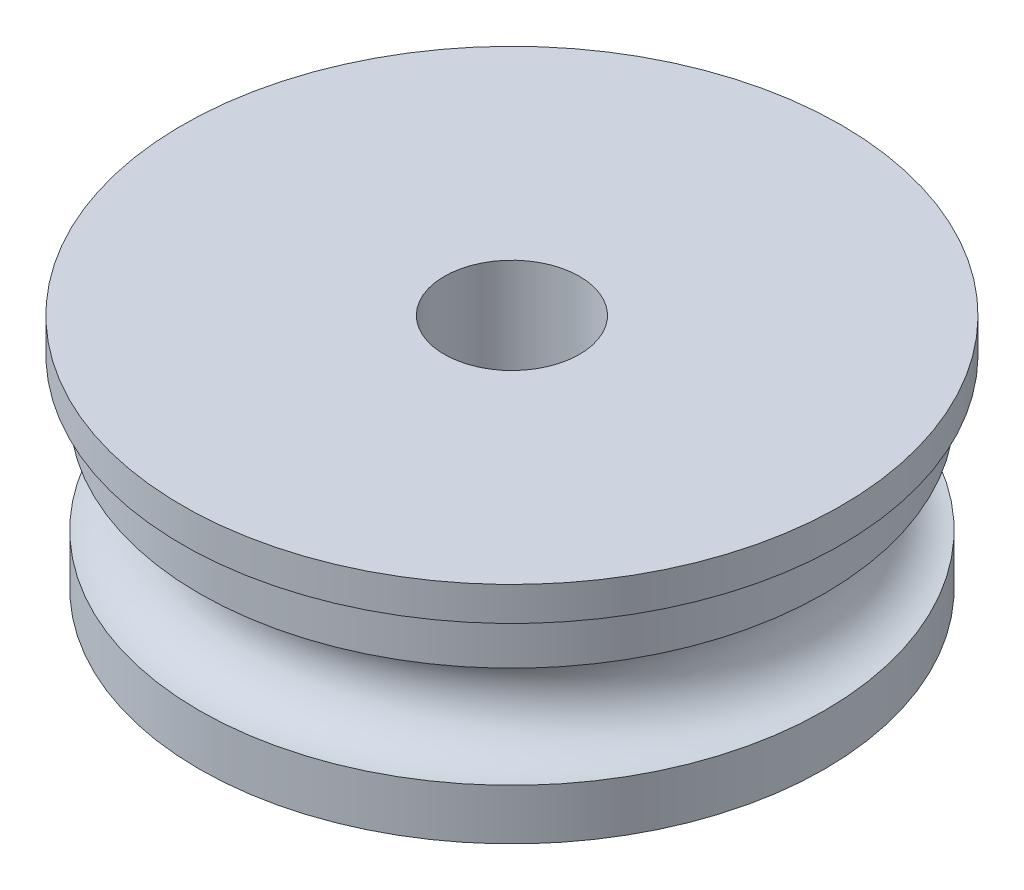
SolidWorks part; units mm, degrees
ref_plane "Front Plane" through (0, 0, 0) normal (0, 0, 1) x (1, 0, 0)
ref_plane "Top Plane" through (0, 0, 0) normal (0, 1, 0) x (1, 0, 0)
ref_plane "Right Plane" through (0, 0, 0) normal (1, 0, 0) x (0, 0, -1)
sketch "Sketch1" plane through (0, 0, 0) normal (0, 0, 1) x (1, 0, 0)
  line L1 (2, 7) -> (9.75, 7)
  line L2 (9.75, 7) -> (9.75, 6)
  line L3 (9.75, 6) -> (9.25, 6)
  line L4 (9.25, 6) -> (9.25, 4.5)
  line L5 (9.25, 0) -> (6, 0)
  line L6 (6, 0) -> (6, 3)
  line L7 (6, 3) -> (2, 3)
  line L9 (0, 0) -> (0, 8.6035) construction
  line L10 (2, 3) -> (2, 7)
  line L11 (9.25, 1.5) -> (9.25, 0)
  arc A0 (9.25, 4.5) -> (9.25, 1.5) centre (9.25, 3) ccw
  point P12 (0, 0)
  point P15 (0, 0)
  point P16 (0, 0)
  point P17 (0, 0)
  point P18 (0, 0)
  point P19 (0, 0)
  point P20 (0, 0)
  point P21 (0, 0)
  dimension "D8" = 3.25
  dimension "D9" = 1.5
  dimension "D1" = 2
  dimension "D2" = 9.75
  dimension "D3" = 9.25
  dimension "D4" = 7
  dimension "D5" = 6
  dimension "D6" = 3
  dimension "D7" = 6
revolve "Revolve1" add sketch "Sketch1" angle 360 about L9
